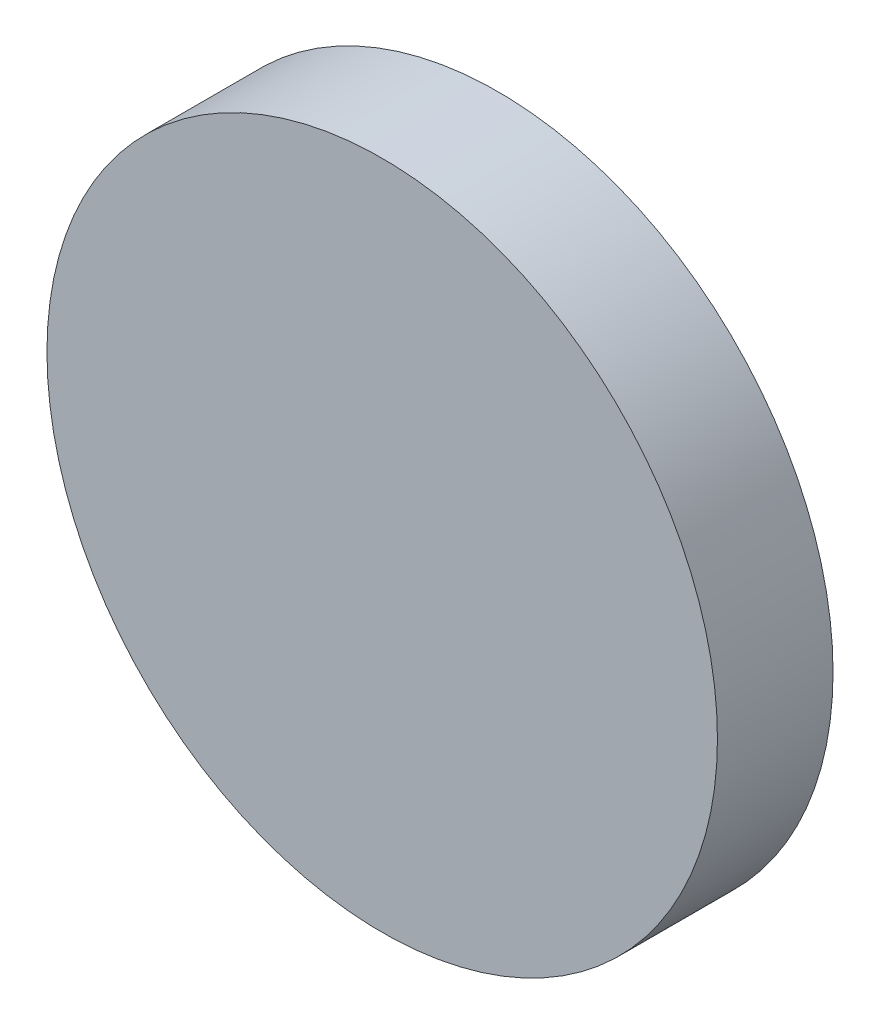
SolidWorks part; units mm, degrees
ref_plane "前视基准面" through (0, 0, 0) normal (0, 0, 1) x (1, 0, 0)
ref_plane "上视基准面" through (0, 0, 0) normal (0, 1, 0) x (1, 0, 0)
ref_plane "右视基准面" through (0, 0, 0) normal (1, 0, 0) x (0, 0, -1)
sketch "草图1" plane through (0, 0, 0) normal (0, 0, 1) x (1, 0, 0)
  circle A0 centre (0, 0) radius 29
  dimension "D1" = 58
extrude "凸台-拉伸1" add sketch "草图1" along normal blind 10
